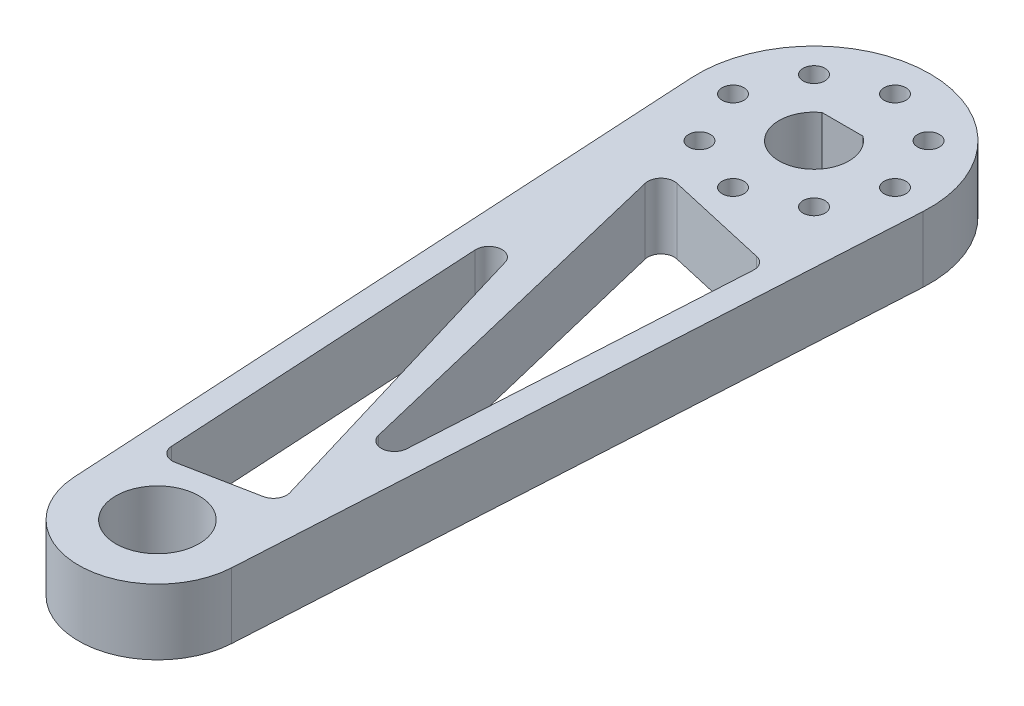
SolidWorks part; units mm, degrees
material "1060 合金"
ref_plane "前视基准面" through (0, 0, 0) normal (0, 0, 1) x (1, 0, 0)
ref_plane "上视基准面" through (0, 0, 0) normal (0, 1, 0) x (1, 0, 0)
ref_plane "右视基准面" through (0, 0, 0) normal (1, 0, 0) x (0, 0, -1)
sketch "草图1" plane through (0, 0, 0) normal (0, 1, 0) x (1, 0, 0)
  line L0 (0, 0) -> (0, 150) construction
  line L1 (-17.9711, -1.02) -> (-26.4574, 148.4983)
  line L2 (17.9711, -1.02) -> (26.4574, 148.4983)
  line L3 (-11.9807, -0.68) -> (-20.4671, 148.8383) construction
  line L4 (11.9807, -0.68) -> (20.4671, 148.8383) construction
  line L5 (-12.741, 12.7148) -> (13.0288, 17.7851) construction
  line L6 (13.0288, 17.7851) -> (18.8303, 120) construction
  line L7 (18.8303, 120) -> (-19.3219, 128.6624) construction
  line L8 (-19.3219, 128.6624) -> (-12.741, 12.7148) construction
  line L9 (13.0288, 17.7851) -> (-19.3219, 128.6624) construction
  line L10 (14.4687, 18.2052) -> (-17.882, 129.0826) construction
  line L12 (-12.741, 12.7148) -> (-18.5544, 115.1395)
  line L13 (-18.5544, 115.1395) -> (10.7129, 17.3294)
  line L14 (10.7129, 17.3294) -> (-12.741, 12.7148)
  line L15 (13.2832, 22.2683) -> (18.8303, 120)
  line L16 (-17.882, 129.0826) -> (-17.7319, 128.5683) construction
  line L17 (18.8303, 120) -> (-12, 127)
  line L18 (-12, 127) -> (13.2832, 22.2683)
  line L19 (0, 156.5) -> (4.6637, 156.5)
  line L20 (0, 156.5) -> (-4.6637, 156.5)
  circle A0 centre (0, 150) radius 26.5 construction
  circle A1 centre (0, 0) radius 18 construction
  circle A2 centre (0, 0) radius 5
  arc A3 (-4.6637, 156.5) -> (4.6637, 156.5) centre (0, 150) ccw
  arc A4 (-17.9711, -1.02) -> (17.9711, -1.02) centre (0, 0) ccw
  arc A5 (-26.4574, 148.4983) -> (26.4574, 148.4983) centre (0, 150) cw
  arc A6 (-20.4671, 148.8383) -> (20.4671, 148.8383) centre (0, 150) cw construction
  arc A7 (-11.9807, -0.68) -> (11.9807, -0.68) centre (0, 0) ccw construction
  dimension "D2" = 53
  dimension "D3" = 36
  dimension "D4" = 10
  dimension "D5" = 16
  dimension "D1" = 150
  dimension "D9" = 30
  dimension "D10" = 23
  dimension "D11" = 12
  dimension "D6" = 6
  dimension "D7" = 1.5
extrude "凸台-拉伸1" add sketch "草图1" along normal blind 15
fillet "圆角1" radius 3 6 edges at (18.8303, 7.5, -120) (-12, 7.5, -127) (-18.5544, 7.5, -115.1395) (-12.741, 7.5, -12.7148) (13.2832, 7.5, -22.2683) (10.7129, 7.5, -17.3294)
sketch "草图2" plane through (0, 15, 0) normal (0, 1, 0) x (1, 0, 0)
  line L0 (0, 150) -> (-18.5, 150) construction
  line L1 (0, 150) -> (18.5, 150) construction
  circle A7 centre (0, 168.5) radius 2.5
  circle A8 centre (13.0815, 163.0815) radius 2.5
  circle A9 centre (18.5, 150) radius 2.5
  circle A10 centre (13.0815, 136.9185) radius 2.5
  circle A11 centre (0, 131.5) radius 2.5
  circle A12 centre (-13.0815, 136.9185) radius 2.5
  circle A13 centre (-18.5, 150) radius 2.5
  circle A14 centre (-13.0815, 163.0815) radius 2.5
  dimension "D2" = 8
  dimension "D1" = 18.5
extrude "切除-拉伸1" cut sketch "草图2" against normal through all
pattern_circular "阵列(圆周)1" [suppressed] count 3 over 360
sketch "草图3" plane through (0, 15, 0) normal (0, 1, 0) x (1, 0, 0)
  line L0 (0, 150) -> (14.25, 150) construction
  circle A0 centre (14.25, 150) radius 2
  dimension "D2" = 4
  dimension "D1" = 14.25
extrude "切除-拉伸2" [suppressed] cut sketch "草图3" against normal through all
pattern_circular "阵列(圆周)2" [suppressed] count 3 over 360
sketch "草图4" plane through (0, 0, 0) normal (0, -1, 0) x (1, 0, 0)
  circle A0 centre (0, 0) radius 9.5
extrude "切除-拉伸3" cut sketch "草图4" against normal blind 20
